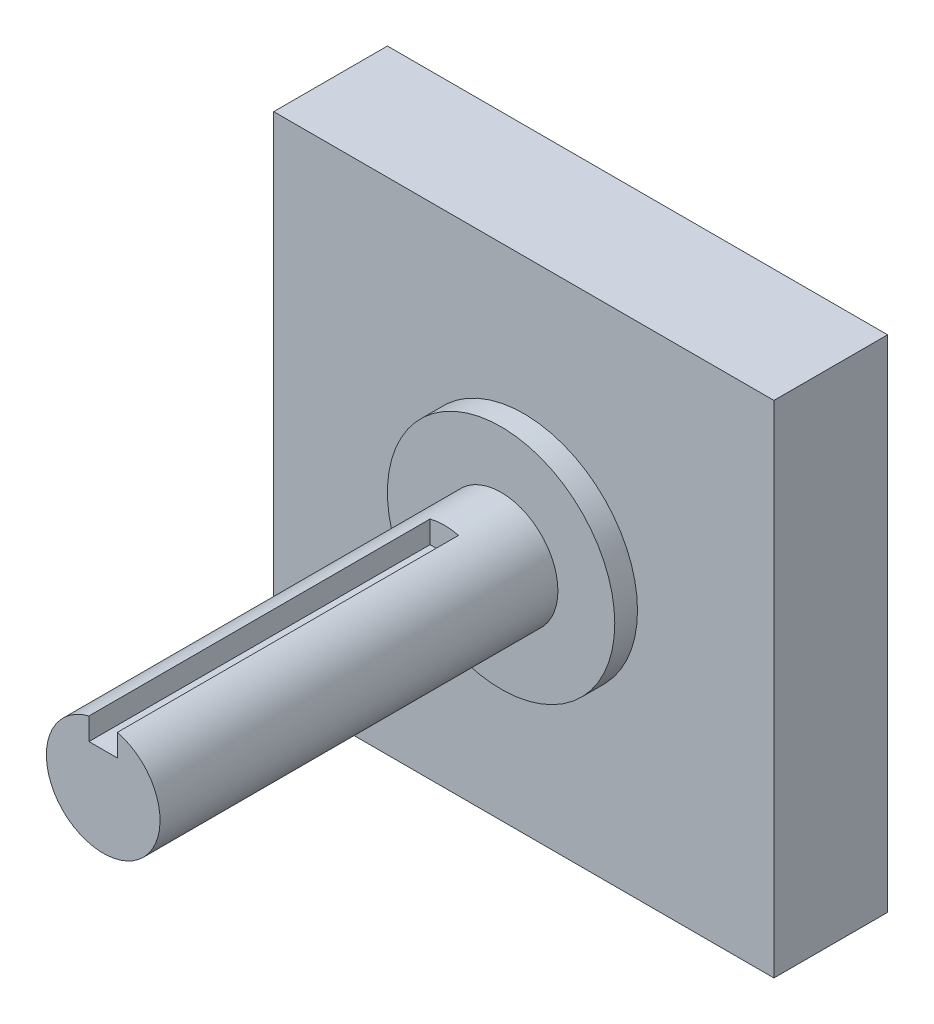
SolidWorks part; units mm, degrees
material "Plain Carbon Steel"
ref_plane "Front Plane" through (0, 0, 0) normal (0, 0, 1) x (1, 0, 0)
ref_plane "Top Plane" through (0, 0, 0) normal (0, 1, 0) x (1, 0, 0)
ref_plane "Right Plane" through (0, 0, 0) normal (1, 0, 0) x (0, 0, -1)
sketch "Sketch1" plane through (0, 0, 0) normal (0, 0, 1) x (1, 0, 0)
  line L1 (-22, 22) -> (22, 22)
  line L2 (-22, 22) -> (-22, -22)
  line L3 (-22, -22) -> (22, -22)
  line L4 (22, 22) -> (22, -22)
  line L5 (-22, 22) -> (22, -22) construction
  line L6 (-22, -22) -> (22, 22) construction
  point P0 (0, 0)
  dimension "D1" = 44
  dimension "D2" = 44
extrude "Boss-Extrude1" add sketch "Sketch1" along normal blind 10
sketch "Sketch2" plane through (0, 0, 10) normal (0, 0, 1) x (1, 0, 0)
  circle A0 centre (0, 0) radius 5
  dimension "D1" = 10
extrude "Boss-Extrude2" add sketch "Sketch2" along normal blind 37
sketch "Sketch3" plane through (0, 0, 0) normal (0, 0, -1) x (-1, 0, 0)
  circle A0 centre (0, 0) radius 5
  dimension "D1" = 10
extrude "Boss-Extrude3" add sketch "Sketch3" against normal blind 3
sketch "Sketch4" plane through (0, 0, 0) normal (0, 0, -1) x (-1, 0, 0)
  circle A0 centre (0, 0) radius 5
  dimension "D1" = 10
extrude "Cut-Extrude1" cut sketch "Sketch4" against normal blind 3
sketch "Sketch5" plane through (-22, 0, 0) normal (-1, 0, 0) x (0, 0, 1)
  circle A0 centre (5, -11) radius 2.5
  circle A1 centre (5, 11) radius 2.5
  dimension "D1" = 5
  dimension "D2" = 5
  dimension "D3" = 22
extrude "Cut-Extrude2" cut sketch "Sketch5" against normal blind 41
sketch "Sketch6" plane through (0, 0, 10) normal (0, 0, 1) x (1, 0, 0)
  circle A0 centre (0, 0) radius 10
  dimension "D1" = 20
extrude "Boss-Extrude4" add sketch "Sketch6" along normal blind 2
sketch "Sketch7" plane through (0, 0, 47) normal (0, 0, 1) x (1, 0, 0)
  line L1 (-1.25, 5.8852) -> (1.25, 5.8852)
  line L2 (-1.25, 5.8852) -> (-1.25, 2.8852)
  line L3 (-1.25, 2.8852) -> (1.25, 2.8852)
  line L4 (1.25, 5.8852) -> (1.25, 2.8852)
  point P4 (0, 5.8852)
  dimension "D1" = 2.5
  dimension "D2" = 3
extrude "Cut-Extrude3" cut sketch "Sketch7" against normal blind 30
